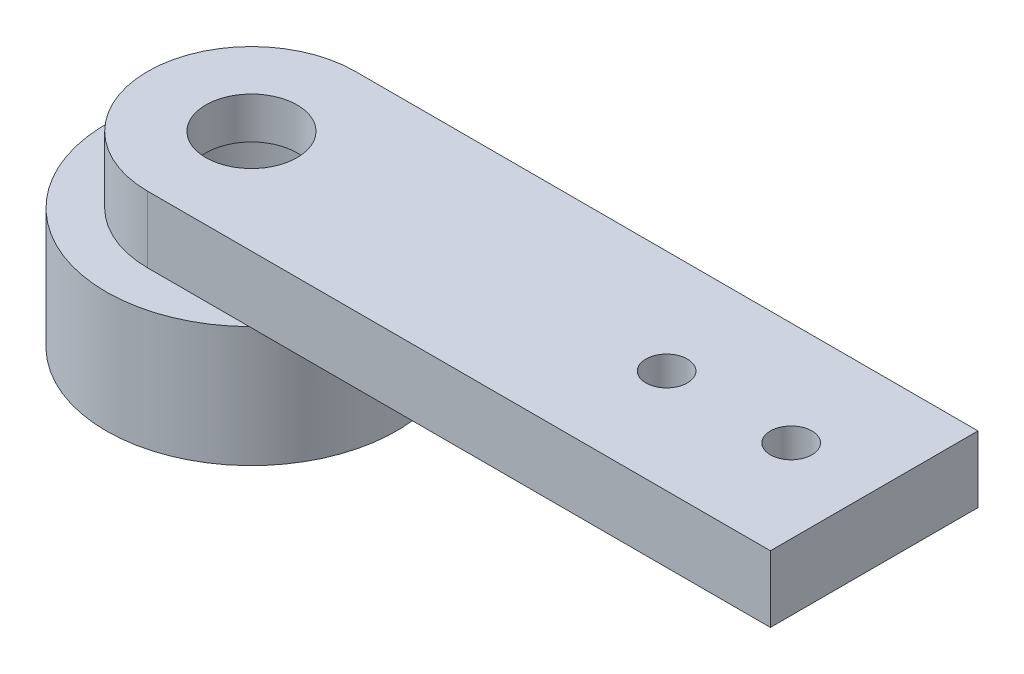
SolidWorks part; units mm, degrees
material "Nylon 6/10"
ref_plane "Front Plane" through (0, 0, 0) normal (0, 0, 1) x (1, 0, 0)
ref_plane "Top Plane" through (0, 0, 0) normal (0, 1, 0) x (1, 0, 0)
ref_plane "Right Plane" through (0, 0, 0) normal (1, 0, 0) x (0, 0, -1)
ref_plane "Y+19_30" through (0, 19.3, 0) normal (0, 1, 0) x (1, 0, 0)
sketch "Sketch1" plane through (0, 19.3, 0) normal (0, 1, 0) x (1, 0, 0)
  line L0 (5.5, -2.5) -> (20.5, -2.5)
  line L1 (20.5, -2.5) -> (20.5, 2.5)
  line L2 (20.5, 2.5) -> (5.5, 2.5)
  arc A0 (5.5, 2.5) -> (5.5, -2.5) centre (5.5, 0) ccw
extrude "Boss-Extrude1" add sketch "Sketch1" along normal blind 1.6
ref_plane "Y+16_40" through (0, 16.4, 0) normal (0, 1, 0) x (1, 0, 0)
sketch "Sketch2" plane through (0, 16.4, 0) normal (0, 1, 0) x (1, 0, 0)
  circle A0 centre (5.5, 0) radius 3.5
extrude "Boss-Extrude2" add sketch "Sketch2" along normal blind 2.9
sketch "Sketch3" plane through (0, 16.4, 0) normal (0, 1, 0) x (1, 0, 0)
  circle A0 centre (5.5, 0) radius 2.425
extrude "Cut-Extrude2" cut sketch "Sketch3" along normal blind 3.5
ref_plane "Y+19_90" through (0, 19.9, 0) normal (0, 1, 0) x (1, 0, 0)
sketch "Sketch4" plane through (0, 19.9, 0) normal (0, 1, 0) x (1, 0, 0)
  circle A0 centre (5.5, 0) radius 1.1
extrude "Cut-Extrude4" cut sketch "Sketch4" along normal blind 1
sketch "Sketch5" plane through (0, 19.3, 0) normal (0, 1, 0) x (1, 0, 0)
  circle A0 centre (15.5, 0) radius 0.5
extrude "Cut-Extrude6" cut sketch "Sketch5" along normal blind 1.6
sketch "Sketch6" plane through (0, 19.3, 0) normal (0, 1, 0) x (1, 0, 0)
  circle A0 centre (18.5, 0) radius 0.5
extrude "Cut-Extrude8" cut sketch "Sketch6" along normal blind 1.6
